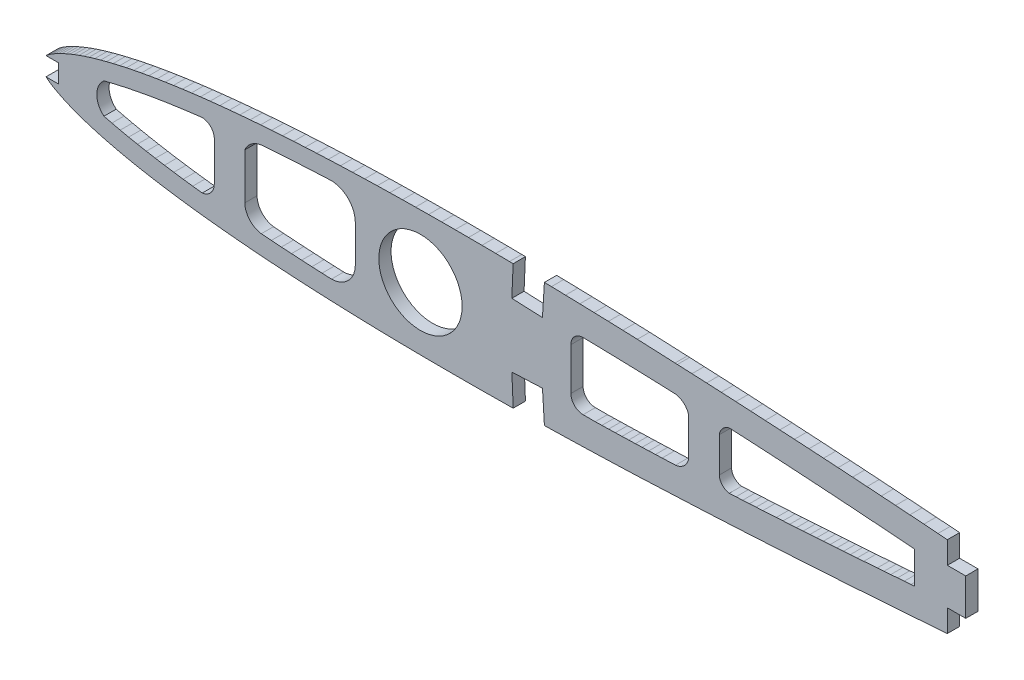
SolidWorks part; units mm, degrees
ref_plane "前视基准面" through (0, 0, 0) normal (0, 0, 1) x (1, 0, 0)
ref_plane "上视基准面" through (0, 0, 0) normal (0, 1, 0) x (1, 0, 0)
ref_plane "右视基准面" through (0, 0, 0) normal (1, 0, 0) x (0, 0, -1)
sketch "Model" plane through (0, 0, 0) normal (0, 0, 1) x (1, 0, 0)
  line L0 (-3.9049, 19.2571) -> (-1.8983, 19.2571)
  line L1 (-1.8983, 19.2571) -> (-1.8983, 22.2571)
  line L2 (-1.8983, 22.2571) -> (-3.9046, 22.2571)
  line L3 (77.4057, 10.6426) -> (77.0934, 15.7631)
  line L4 (77.0934, 15.7631) -> (72.0984, 15.5451)
  line L5 (72.0984, 15.5451) -> (72.3163, 10.5512)
  line L6 (77.4057, 30.8706) -> (77.0837, 25.7411)
  line L7 (77.0837, 25.7411) -> (72.0877, 25.9591)
  line L8 (72.0877, 25.9591) -> (72.3069, 30.9622)
  line L9 (143.1437, 14.1246) -> (141.6177, 14.0089)
  line L10 (141.6177, 14.0089) -> (139.3227, 13.8379)
  line L11 (139.3227, 13.8379) -> (137.0277, 13.6699)
  line L12 (137.0277, 13.6699) -> (134.6947, 13.5019)
  line L13 (134.6947, 13.5019) -> (132.3627, 13.3379)
  line L14 (132.3627, 13.3379) -> (130.0297, 13.1759)
  line L15 (130.0297, 13.1759) -> (127.6687, 13.0159)
  line L16 (127.6687, 13.0159) -> (125.3097, 12.8589)
  line L17 (125.3097, 12.8589) -> (122.9487, 12.7059)
  line L18 (122.9487, 12.7059) -> (120.5687, 12.5579)
  line L19 (120.5687, 12.5579) -> (118.1897, 12.4139)
  line L20 (118.1897, 12.4139) -> (115.8087, 12.2729)
  line L21 (115.8087, 12.2729) -> (113.4207, 12.1329)
  line L22 (113.4207, 12.1329) -> (111.0327, 11.9959)
  line L23 (111.0327, 11.9959) -> (108.6437, 11.8639)
  line L24 (108.6437, 11.8639) -> (106.2557, 11.7369)
  line L25 (106.2557, 11.7369) -> (103.8677, 11.6159)
  line L26 (103.8677, 11.6159) -> (101.4787, 11.5009)
  line L27 (101.4787, 11.5009) -> (99.0987, 11.3919)
  line L28 (99.0987, 11.3919) -> (98.7169, 11.375)
  line L29 (98.7169, 11.375) -> (92.5667, 11.0971)
  line L30 (92.5667, 11.0971) -> (90.2067, 11.0101)
  line L31 (90.2067, 11.0101) -> (87.8457, 10.9281)
  line L32 (87.8457, 10.9281) -> (85.5127, 10.8531)
  line L33 (85.5127, 10.8531) -> (83.1807, 10.7851)
  line L34 (83.1807, 10.7851) -> (80.8477, 10.7221)
  line L35 (80.8477, 10.7221) -> (78.5527, 10.6671)
  line L36 (78.5527, 10.6671) -> (77.4057, 10.6426)
  line L37 (72.3163, 10.5512) -> (71.7147, 10.5421)
  line L38 (71.7147, 10.5421) -> (69.4667, 10.5161)
  line L39 (69.4667, 10.5161) -> (67.2177, 10.4961)
  line L40 (67.2177, 10.4961) -> (65.0247, 10.4851)
  line L41 (65.0247, 10.4851) -> (62.8317, 10.4811)
  line L42 (62.8317, 10.4811) -> (60.6377, 10.4851)
  line L43 (60.6377, 10.4851) -> (58.5077, 10.4971)
  line L44 (58.5077, 10.4971) -> (56.3787, 10.5161)
  line L45 (56.3787, 10.5161) -> (54.2487, 10.5441)
  line L46 (54.2487, 10.5441) -> (52.1917, 10.5801)
  line L47 (52.1917, 10.5801) -> (50.1357, 10.6251)
  line L48 (50.1357, 10.6251) -> (48.0787, 10.6791)
  line L49 (48.0787, 10.6791) -> (46.1017, 10.7401)
  line L50 (46.1017, 10.7401) -> (44.1247, 10.8101)
  line L51 (44.1247, 10.8101) -> (42.1487, 10.8891)
  line L52 (42.1487, 10.8891) -> (40.2587, 10.9741)
  line L53 (40.2587, 10.9741) -> (38.3707, 11.0691)
  line L54 (38.3707, 11.0691) -> (36.4827, 11.1741)
  line L55 (36.4827, 11.1741) -> (34.6897, 11.2851)
  line L56 (34.6897, 11.2851) -> (32.8967, 11.4051)
  line L57 (32.8967, 11.4051) -> (31.1047, 11.5371)
  line L58 (31.1047, 11.5371) -> (29.4137, 11.6721)
  line L59 (29.4137, 11.6721) -> (27.7247, 11.8181)
  line L60 (27.7247, 11.8181) -> (26.0357, 11.9761)
  line L61 (26.0357, 11.9761) -> (24.4527, 12.1341)
  line L62 (24.4527, 12.1341) -> (22.8727, 12.3031)
  line L63 (22.8727, 12.3031) -> (21.2927, 12.4851)
  line L64 (21.2927, 12.4851) -> (19.8257, 12.6651)
  line L65 (19.8257, 12.6651) -> (18.3617, 12.8581)
  line L66 (18.3617, 12.8581) -> (16.8987, 13.0641)
  line L67 (16.8987, 13.0641) -> (15.5527, 13.2671)
  line L68 (15.5527, 13.2671) -> (14.2107, 13.4821)
  line L69 (14.2107, 13.4821) -> (12.8697, 13.7101)
  line L70 (12.8697, 13.7101) -> (11.6497, 13.9311)
  line L71 (11.6497, 13.9311) -> (10.4337, 14.1661)
  line L72 (10.4337, 14.1661) -> (9.2197, 14.4161)
  line L73 (9.2197, 14.4161) -> (8.1307, 14.6541)
  line L74 (8.1307, 14.6541) -> (7.0457, 14.9071)
  line L75 (7.0457, 14.9071) -> (5.9647, 15.1761)
  line L76 (5.9647, 15.1761) -> (5.0107, 15.4271)
  line L77 (5.0107, 15.4271) -> (4.0607, 15.6931)
  line L78 (4.0607, 15.6931) -> (3.1157, 15.9771)
  line L79 (3.1157, 15.9771) -> (2.2997, 16.2391)
  line L80 (2.2997, 16.2391) -> (1.4897, 16.5181)
  line L81 (1.4897, 16.5181) -> (0.6877, 16.8171)
  line L82 (0.6877, 16.8171) -> (0.0137, 17.0871)
  line L83 (0.0137, 17.0871) -> (-0.6523, 17.3731)
  line L84 (-0.6523, 17.3731) -> (-1.3123, 17.6751)
  line L85 (-1.3123, 17.6751) -> (-1.8433, 17.9351)
  line L86 (-1.8433, 17.9351) -> (-2.3653, 18.2111)
  line L87 (-2.3653, 18.2111) -> (-2.8763, 18.5111)
  line L88 (-2.8763, 18.5111) -> (-3.2653, 18.7651)
  line L89 (-3.2653, 18.7651) -> (-3.6413, 19.0391)
  line L90 (-3.6413, 19.0391) -> (-3.9049, 19.2571)
  line L91 (-3.9046, 22.2571) -> (-3.6413, 22.4741)
  line L92 (-3.6413, 22.4741) -> (-3.2653, 22.7481)
  line L93 (-3.2653, 22.7481) -> (-2.8763, 23.0031)
  line L94 (-2.8763, 23.0031) -> (-2.3653, 23.3021)
  line L95 (-2.3653, 23.3021) -> (-1.8433, 23.5791)
  line L96 (-1.8433, 23.5791) -> (-1.3123, 23.8381)
  line L97 (-1.3123, 23.8381) -> (-0.6523, 24.1411)
  line L98 (-0.6523, 24.1411) -> (0.0137, 24.4271)
  line L99 (0.0137, 24.4271) -> (0.6877, 24.6961)
  line L100 (0.6877, 24.6961) -> (1.4897, 24.9951)
  line L101 (1.4897, 24.9951) -> (2.2997, 25.2741)
  line L102 (2.2997, 25.2741) -> (3.1157, 25.5361)
  line L103 (3.1157, 25.5361) -> (4.0607, 25.8201)
  line L104 (4.0607, 25.8201) -> (5.0107, 26.0861)
  line L105 (5.0107, 26.0861) -> (5.9647, 26.3381)
  line L106 (5.9647, 26.3381) -> (7.0457, 26.6061)
  line L107 (7.0457, 26.6061) -> (8.1307, 26.8591)
  line L108 (8.1307, 26.8591) -> (9.2197, 27.0981)
  line L109 (9.2197, 27.0981) -> (10.4337, 27.3481)
  line L110 (10.4337, 27.3481) -> (11.6497, 27.5821)
  line L111 (11.6497, 27.5821) -> (12.8697, 27.8031)
  line L112 (12.8697, 27.8031) -> (14.2107, 28.0321)
  line L113 (14.2107, 28.0321) -> (15.5527, 28.2471)
  line L114 (15.5527, 28.2471) -> (16.8987, 28.4491)
  line L115 (16.8987, 28.4491) -> (18.3617, 28.6551)
  line L116 (18.3617, 28.6551) -> (19.8257, 28.8481)
  line L117 (19.8257, 28.8481) -> (21.2927, 29.0291)
  line L118 (21.2927, 29.0291) -> (22.8727, 29.2101)
  line L119 (22.8727, 29.2101) -> (24.4527, 29.3801)
  line L120 (24.4527, 29.3801) -> (26.0357, 29.5381)
  line L121 (26.0357, 29.5381) -> (27.7247, 29.6951)
  line L122 (27.7247, 29.6951) -> (29.4137, 29.8411)
  line L123 (29.4137, 29.8411) -> (31.1047, 29.9761)
  line L124 (31.1047, 29.9761) -> (32.8967, 30.1081)
  line L125 (32.8967, 30.1081) -> (34.6897, 30.2291)
  line L126 (34.6897, 30.2291) -> (36.4827, 30.3391)
  line L127 (36.4827, 30.3391) -> (38.3707, 30.4441)
  line L128 (38.3707, 30.4441) -> (40.2587, 30.5391)
  line L129 (40.2587, 30.5391) -> (42.1487, 30.6241)
  line L130 (42.1487, 30.6241) -> (44.1247, 30.7041)
  line L131 (44.1247, 30.7041) -> (46.1017, 30.7741)
  line L132 (46.1017, 30.7741) -> (48.0787, 30.8341)
  line L133 (48.0787, 30.8341) -> (50.1357, 30.8881)
  line L134 (50.1357, 30.8881) -> (52.1917, 30.9331)
  line L135 (52.1917, 30.9331) -> (54.2487, 30.9691)
  line L136 (54.2487, 30.9691) -> (56.3787, 30.9971)
  line L137 (56.3787, 30.9971) -> (58.5077, 31.0171)
  line L138 (58.5077, 31.0171) -> (60.6377, 31.0281)
  line L139 (60.6377, 31.0281) -> (62.8317, 31.0321)
  line L140 (62.8317, 31.0321) -> (65.0247, 31.0281)
  line L141 (65.0247, 31.0281) -> (67.2177, 31.0171)
  line L142 (67.2177, 31.0171) -> (69.4667, 30.9981)
  line L143 (69.4667, 30.9981) -> (71.7147, 30.9711)
  line L144 (71.7147, 30.9711) -> (72.3069, 30.9622)
  line L145 (77.4057, 30.8706) -> (78.5527, 30.8461)
  line L146 (78.5527, 30.8461) -> (80.8477, 30.7911)
  line L147 (80.8477, 30.7911) -> (83.1807, 30.7291)
  line L148 (83.1807, 30.7291) -> (85.5127, 30.6601)
  line L149 (85.5127, 30.6601) -> (87.8457, 30.5861)
  line L150 (87.8457, 30.5861) -> (90.2067, 30.5041)
  line L151 (90.2067, 30.5041) -> (92.5667, 30.4161)
  line L152 (92.5667, 30.4161) -> (98.7168, 30.1346)
  line L153 (98.7168, 30.1346) -> (99.0987, 30.1179)
  line L154 (99.0987, 30.1179) -> (101.4787, 30.0079)
  line L155 (101.4787, 30.0079) -> (103.8677, 29.8929)
  line L156 (103.8677, 29.8929) -> (106.2557, 29.7719)
  line L157 (106.2557, 29.7719) -> (108.6437, 29.6449)
  line L158 (108.6437, 29.6449) -> (111.0327, 29.5129)
  line L159 (111.0327, 29.5129) -> (113.4207, 29.3759)
  line L160 (113.4207, 29.3759) -> (115.8087, 29.2369)
  line L161 (115.8087, 29.2369) -> (118.1897, 29.0959)
  line L162 (118.1897, 29.0959) -> (120.5687, 28.9519)
  line L163 (120.5687, 28.9519) -> (122.9487, 28.8029)
  line L164 (122.9487, 28.8029) -> (125.3097, 28.6509)
  line L165 (125.3097, 28.6509) -> (127.6687, 28.4939)
  line L166 (127.6687, 28.4939) -> (130.0297, 28.3329)
  line L167 (130.0297, 28.3329) -> (132.3627, 28.1709)
  line L168 (132.3627, 28.1709) -> (134.6947, 28.0069)
  line L169 (134.6947, 28.0069) -> (137.0277, 27.8399)
  line L170 (137.0277, 27.8399) -> (139.3227, 27.6719)
  line L171 (139.3227, 27.6719) -> (141.6177, 27.5009)
  line L172 (141.6177, 27.5009) -> (143.1437, 27.3845)
  line L173 (5.5487, 23.4121) -> (6.8406, 23.7351)
  line L174 (6.8406, 23.7351) -> (8.2036, 24.0499)
  line L175 (8.2036, 24.0499) -> (9.5805, 24.347)
  line L176 (9.5805, 24.347) -> (11.0087, 24.6327)
  line L177 (11.0087, 24.6327) -> (12.4548, 24.903)
  line L178 (12.4548, 24.903) -> (13.9349, 25.1624)
  line L179 (13.9349, 25.1624) -> (15.4192, 25.4038)
  line L180 (15.4192, 25.4038) -> (16.941, 25.6336)
  line L181 (16.941, 25.6336) -> (18.4729, 25.8508)
  line L182 (18.4729, 25.8508) -> (20.0266, 26.0567)
  line L183 (20.0266, 26.0567) -> (21.5843, 26.2491)
  line L184 (31.2133, 27.1847) -> (32.8548, 27.3081)
  line L185 (32.8548, 27.3081) -> (34.4918, 27.4219)
  line L186 (34.4918, 27.4219) -> (36.1429, 27.5267)
  line L187 (36.1429, 27.5267) -> (37.8021, 27.6248)
  line L188 (37.8021, 27.6248) -> (39.4612, 27.7157)
  line L189 (39.4612, 27.7157) -> (41.1277, 27.7975)
  line L190 (41.1277, 27.7975) -> (42.6609, 27.8683)
  line L191 (46.5564, 23.9037) -> (46.5564, 17.9276)
  line L192 (42.6609, 13.963) -> (41.1277, 14.0337)
  line L193 (41.1277, 14.0337) -> (39.4612, 14.1156)
  line L194 (39.4612, 14.1156) -> (37.8021, 14.2064)
  line L195 (37.8021, 14.2064) -> (36.1429, 14.3046)
  line L196 (36.1429, 14.3046) -> (34.4918, 14.4094)
  line L197 (34.4918, 14.4094) -> (32.8548, 14.5232)
  line L198 (32.8548, 14.5232) -> (31.2133, 14.6466)
  line L199 (21.5843, 15.5821) -> (20.0266, 15.7746)
  line L200 (20.0266, 15.7746) -> (18.4729, 15.9805)
  line L201 (18.4729, 15.9805) -> (16.941, 16.1977)
  line L202 (16.941, 16.1977) -> (15.4192, 16.4275)
  line L203 (15.4192, 16.4275) -> (13.9349, 16.6688)
  line L204 (13.9349, 16.6688) -> (12.4548, 16.9283)
  line L205 (12.4548, 16.9283) -> (11.0087, 17.1986)
  line L206 (11.0087, 17.1986) -> (9.5805, 17.4843)
  line L207 (9.5805, 17.4843) -> (8.2036, 17.7814)
  line L208 (8.2036, 17.7814) -> (6.8406, 18.0962)
  line L209 (6.8406, 18.0962) -> (5.5487, 18.4192)
  line L211 (143.1437, 14.1246) -> (143.1437, 17.765)
  line L212 (143.1437, 17.765) -> (146.1437, 17.765)
  line L213 (146.1437, 17.765) -> (146.1437, 23.765)
  line L214 (146.1437, 23.765) -> (143.1437, 23.765)
  line L215 (143.1437, 23.765) -> (143.1437, 27.3845)
  line L217 (137.7615, 23.3908) -> (137.2097, 23.434)
  line L218 (137.2097, 23.434) -> (136.1123, 23.5188)
  line L219 (136.1123, 23.5188) -> (135.0132, 23.6025)
  line L220 (135.0132, 23.6025) -> (133.9104, 23.6853)
  line L221 (133.9104, 23.6853) -> (132.8095, 23.7692)
  line L222 (132.8095, 23.7692) -> (131.7124, 23.8504)
  line L223 (131.7124, 23.8504) -> (130.6115, 23.9306)
  line L224 (130.6115, 23.9306) -> (129.5104, 24.0109)
  line L225 (129.5104, 24.0109) -> (128.4126, 24.0898)
  line L226 (128.4126, 24.0898) -> (127.3118, 24.1677)
  line L227 (127.3118, 24.1677) -> (126.2137, 24.2454)
  line L228 (126.2137, 24.2454) -> (125.1159, 24.3208)
  line L229 (125.1159, 24.3208) -> (124.0152, 24.3962)
  line L230 (124.0152, 24.3962) -> (122.9172, 24.4704)
  line L231 (122.9172, 24.4704) -> (121.8194, 24.5433)
  line L232 (121.8194, 24.5433) -> (120.7215, 24.6151)
  line L233 (120.7215, 24.6151) -> (119.6249, 24.6857)
  line L234 (119.6249, 24.6857) -> (118.5272, 24.755)
  line L235 (118.5272, 24.755) -> (117.4275, 24.8233)
  line L236 (117.4275, 24.8233) -> (116.3307, 24.8915)
  line L237 (116.3307, 24.8915) -> (115.2348, 24.9571)
  line L238 (115.2348, 24.9571) -> (114.1362, 25.0218)
  line L239 (114.1362, 25.0218) -> (113.0396, 25.0864)
  line L240 (113.0396, 25.0864) -> (111.9449, 25.1485)
  line L241 (111.9449, 25.1485) -> (110.8483, 25.2095)
  line L242 (110.8483, 25.2095) -> (109.7517, 25.2692)
  line L243 (109.7517, 25.2692) -> (108.657, 25.3277)
  line L244 (108.657, 25.3277) -> (107.5604, 25.3839)
  line L245 (98.8011, 25.7878) -> (96.6134, 25.8738)
  line L246 (96.6134, 25.8738) -> (95.5199, 25.9144)
  line L247 (95.5199, 25.9144) -> (94.4275, 25.9526)
  line L248 (94.4275, 25.9526) -> (93.3353, 25.9896)
  line L249 (93.3353, 25.9896) -> (92.243, 26.0243)
  line L250 (92.243, 26.0243) -> (91.1488, 26.0577)
  line L251 (91.1488, 26.0577) -> (90.0584, 26.0899)
  line L252 (90.0584, 26.0899) -> (88.9692, 26.1185)
  line L253 (88.9692, 26.1185) -> (87.8762, 26.146)
  line L254 (87.8762, 26.146) -> (86.7863, 26.1723)
  line L255 (86.7863, 26.1723) -> (85.6972, 26.1961)
  line L256 (85.6972, 26.1961) -> (84.6092, 26.2176)
  line L257 (84.6092, 26.2176) -> (83.7579, 26.2325)
  line L258 (81.7229, 24.2328) -> (81.7229, 17.3338)
  line L259 (83.7229, 15.3338) -> (85.6978, 15.3338)
  line L260 (85.6978, 15.3338) -> (86.7863, 15.3576)
  line L261 (86.7863, 15.3576) -> (87.8762, 15.3839)
  line L262 (87.8762, 15.3839) -> (88.9692, 15.4114)
  line L263 (88.9692, 15.4114) -> (90.0584, 15.44)
  line L264 (90.0584, 15.44) -> (91.1488, 15.4722)
  line L265 (91.1488, 15.4722) -> (92.243, 15.5057)
  line L266 (92.243, 15.5057) -> (93.3353, 15.5403)
  line L267 (93.3353, 15.5403) -> (94.4275, 15.5773)
  line L268 (94.4275, 15.5773) -> (95.5199, 15.6155)
  line L269 (95.5199, 15.6155) -> (96.6134, 15.6561)
  line L270 (96.6134, 15.6561) -> (98.8011, 15.7421)
  line L271 (107.5604, 16.146) -> (108.657, 16.2022)
  line L272 (108.657, 16.2022) -> (109.7517, 16.2607)
  line L273 (109.7517, 16.2607) -> (110.8483, 16.3205)
  line L274 (110.8483, 16.3205) -> (111.9449, 16.3815)
  line L275 (111.9449, 16.3815) -> (113.0396, 16.4435)
  line L276 (113.0396, 16.4435) -> (114.1362, 16.5081)
  line L277 (114.1362, 16.5081) -> (115.2348, 16.5728)
  line L278 (115.2348, 16.5728) -> (116.3307, 16.6385)
  line L279 (116.3307, 16.6385) -> (117.4275, 16.7066)
  line L280 (117.4275, 16.7066) -> (118.5272, 16.7749)
  line L281 (118.5272, 16.7749) -> (119.6249, 16.8443)
  line L282 (119.6249, 16.8443) -> (120.7215, 16.9148)
  line L283 (120.7215, 16.9148) -> (121.8194, 16.9866)
  line L284 (121.8194, 16.9866) -> (122.9172, 17.0595)
  line L285 (122.9172, 17.0595) -> (124.0152, 17.1337)
  line L286 (124.0152, 17.1337) -> (125.1159, 17.2091)
  line L287 (125.1159, 17.2091) -> (126.2137, 17.2845)
  line L288 (126.2137, 17.2845) -> (127.3118, 17.3622)
  line L289 (127.3118, 17.3622) -> (128.4126, 17.4401)
  line L290 (128.4126, 17.4401) -> (129.5104, 17.519)
  line L291 (129.5104, 17.519) -> (130.6115, 17.5993)
  line L292 (130.6115, 17.5993) -> (131.7124, 17.6796)
  line L293 (131.7124, 17.6796) -> (132.8095, 17.7607)
  line L294 (132.8095, 17.7607) -> (133.9104, 17.8446)
  line L295 (133.9104, 17.8446) -> (135.0132, 17.9274)
  line L296 (135.0132, 17.9274) -> (136.1123, 18.0111)
  line L297 (136.1123, 18.0111) -> (137.2097, 18.0959)
  line L298 (137.2097, 18.0959) -> (137.7615, 18.1391)
  line L299 (137.7615, 23.3908) -> (137.7615, 18.1391)
  line L300 (23.5484, 24.1411) -> (23.5484, 17.8821)
  line L301 (100.9361, 23.8887) -> (100.9361, 17.7068)
  line L302 (28.5243, 25.1536) -> (28.5243, 17.6661)
  line L303 (105.9307, 23.6046) -> (105.9307, 17.9162)
  arc A0 (5.5487, 23.4121) -> (5.5487, 18.4192) centre (7.64, 20.9156) ccw
  circle A1 centre (57.1843, 20.7571) radius 6.7943
  arc A2 (21.5843, 15.5821) -> (23.5484, 17.8821) centre (21.2638, 17.8444) ccw
  arc A3 (28.5243, 17.6661) -> (31.2133, 14.6466) centre (31.6431, 17.7364) ccw
  arc A4 (23.5484, 24.1411) -> (21.5843, 26.2491) centre (21.5314, 24.2309) ccw
  arc A5 (31.2133, 27.1847) -> (28.5243, 25.1536) centre (31.6694, 23.7853) ccw
  arc A6 (98.8011, 15.7421) -> (100.9361, 17.7068) centre (98.5528, 18.1542) ccw
  arc A7 (105.9307, 17.9162) -> (107.5604, 16.146) centre (107.8246, 18.0245) ccw
  arc A8 (100.9361, 23.8887) -> (98.8011, 25.7878) centre (98.4571, 23.2514) ccw
  arc A9 (107.5604, 25.3839) -> (105.9307, 23.6046) centre (108.0596, 23.2907) ccw
  arc A10 (46.5564, 23.9037) -> (42.6609, 27.8683) centre (42.5912, 23.9037) ccw
  arc A11 (42.6609, 13.963) -> (46.5564, 17.9276) centre (42.5912, 17.9276) ccw
  arc A12 (83.7579, 26.2325) -> (81.7229, 24.2328) centre (83.7229, 24.2328) ccw
  arc A13 (81.7229, 17.3338) -> (83.7229, 15.3338) centre (83.7229, 17.3338) ccw
  point P7 (0, 0)
  point P9 (23.7797, 24.1411)
  point P12 (77.4057, 10.6549)
  point P45 (72.5331, 10.5512)
  point P48 (77.4057, 30.7911)
  point P49 (72.5256, 30.9622)
  point P52 (137.7615, 23.434)
  point P251 (23.5659, 17.8821)
  point P256 (0, 0)
  point P285 (0, 0)
  point P341 (0, 0)
  point P342 (98.8011, 25.8046)
  point P343 (0, 0)
  point P344 (28.5243, 17.4843)
extrude "凸台-拉伸1" add sketch "Model" along normal blind 2
